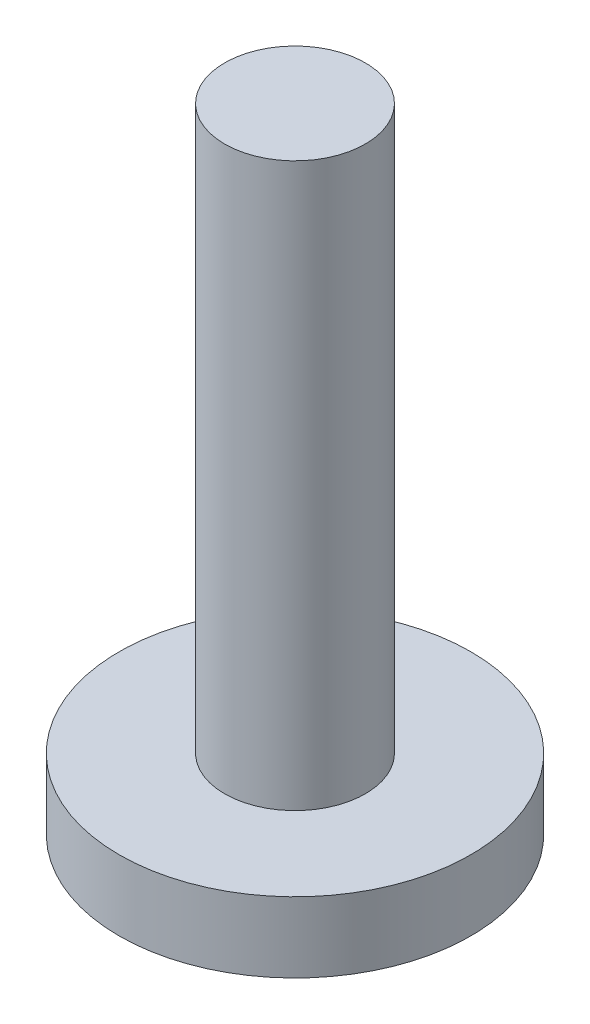
SolidWorks part; units mm, degrees
ref_plane "Front Plane" through (0, 0, 0) normal (0, 0, 1) x (1, 0, 0)
ref_plane "Top Plane" through (0, 0, 0) normal (0, 1, 0) x (1, 0, 0)
ref_plane "Right Plane" through (0, 0, 0) normal (1, 0, 0) x (0, 0, -1)
sketch "Sketch1" plane through (0, 0, 0) normal (0, 1, 0) x (1, 0, 0)
  circle A0 centre (0, 0) radius 0.5
  dimension "D1" = 1
extrude "Boss-Extrude1" add sketch "Sketch1" along normal blind 4
sketch "Sketch2" plane through (0, 0, 0) normal (0, -1, 0) x (1, 0, 0)
  circle A0 centre (0, 0) radius 1.25
  dimension "D1" = 2.5
extrude "Boss-Extrude2" add sketch "Sketch2" along normal blind 0.5
sketch "Sketch3" plane through (0, -0.5, 0) normal (0, -1, 0) x (1, 0, 0)
  line L0 (0, 0) -> (0, 1.25) construction
  line L1 (0, 0) -> (1.25, 0) construction
  line L2 (-0.05, 0.85) -> (0.05, 0.85)
  line L3 (0.05, 0.85) -> (0.05, 0.05)
  line L4 (0.05, 0.05) -> (0.85, 0.05)
  line L5 (0.85, 0.05) -> (0.85, -0.05)
  line L6 (0.05, -0.05) -> (0.85, -0.05)
  line L7 (0.05, -0.85) -> (0.05, -0.05)
  line L8 (-0.05, -0.85) -> (0.05, -0.85)
  line L9 (-0.05, -0.85) -> (-0.05, -0.05)
  line L10 (-0.05, -0.05) -> (-0.85, -0.05)
  line L11 (-0.85, 0.05) -> (-0.85, -0.05)
  line L12 (-0.05, 0.05) -> (-0.85, 0.05)
  line L13 (-0.05, 0.85) -> (-0.05, 0.05)
  circle A0 centre (0, 0) radius 1.25 construction
  point P13 (0.85, 0)
  point P17 (0, -0.85)
  point P22 (0, 0.85)
  dimension "D1" = 0.05
  dimension "D2" = 0.05
  dimension "D3" = 0.8
  dimension "D4" = 0.8
extrude "Cut-Extrude1" cut sketch "Sketch3" against normal blind 0.3
